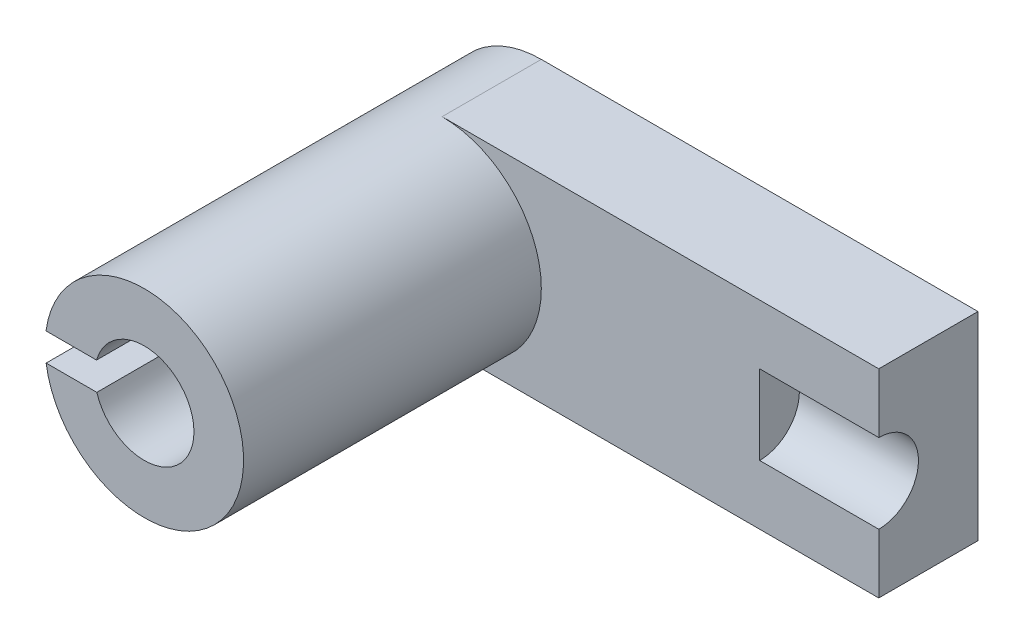
SolidWorks part; units mm, degrees
ref_plane "Front Plane" through (0, 0, 0) normal (1, 0, 0) x (0, 1, 0)
ref_plane "Top Plane" through (0, 0, 0) normal (0, 0, 1) x (0, 1, 0)
ref_plane "Right Plane" through (0, 0, 0) normal (0, 1, 0) x (-1, 0, 0)
sketch "Sketch1" plane through (0, 0, 0) normal (1, 0, 0) x (0, 1, 0)
  line L0 (-92.7928, 0) -> (90.3153, 0) construction
  line L1 (0, 84.1216) -> (0, -87.2748) construction
  line L2 (-10, 12.5) -> (-25, 12.5)
  line L3 (25, -12.5) -> (-25, -12.5)
  line L4 (25, -12.5) -> (25, 12.5)
  line L5 (25, 12.5) -> (10, 12.5)
  line L6 (-25, -12.5) -> (-25, 12.5)
  line L7 (25, -12.5) -> (-25, 12.5) construction
  line L8 (25, 12.5) -> (-25, -12.5) construction
  line L9 (-10, 12.5) -> (10, 12.5)
  arc A0 (-10, 12.5) -> (10, 12.5) centre (0, 12.5) ccw
  point P5 (0, 0)
  point P13 (0, 0)
  dimension "D3" = 10
  dimension "D1" = 25
  dimension "D2" = 50
extrude "Boss-Extrude1" add sketch "Sketch1" against normal blind 110 contours A0 L5 L6 L3 L4 | L5 A0
sketch "Sketch4" plane through (0, 0, 0) normal (1, 0, 0) x (0, 1, 0)
  line L0 (25, 12.5) -> (-25, 12.5) construction
  line L1 (-10, 12.5) -> (10, 12.5)
  arc A0 (-10, 12.5) -> (10, 12.5) centre (0, 12.5) ccw
  dimension "D1" = 10
extrude "Cut-Extrude1" cut sketch "Sketch4" against normal blind 30 and the other way through all
sketch "Sketch5" plane through (0, 0, -12.5) normal (0, 0, -1) x (1, 0, 0)
  line L0 (-110, -25) -> (-110, 25) construction
  circle A0 centre (-110, 0) radius 25
  circle A1 centre (-110, 0) radius 12.5
  dimension "D1" = 25
extrude "Boss-Extrude2" add sketch "Sketch5" against normal blind 100
sketch "Sketch6" plane through (0, 0, 87.5) normal (0, 0, 1) x (1, 0, 0)
  line L0 (-110, -3.6171) -> (-110, 3.3829)
  line L1 (-110, 12.5) -> (-110, -12.5) construction
  line L2 (-110, 3.3829) -> (-142.2039, 3.3829)
  line L3 (-142.2039, 3.3829) -> (-142.2039, -3.6171)
  line L4 (-142.2039, -3.6171) -> (-110, -3.6171)
  point P5 (-110, -0.1171)
extrude "Cut-Extrude2" cut sketch "Sketch6" against normal through all both and the other way through all
sketch "Sketch7" plane through (0, 0, 87.5) normal (0, 0, 1) x (1, 0, 0)
  line L0 (-110, 12.5) -> (-110, -12.5) construction
  circle A0 centre (-110, 0) radius 12.5
extrude "Cut-Extrude3" cut sketch "Sketch7" against normal through all both and the other way through all
